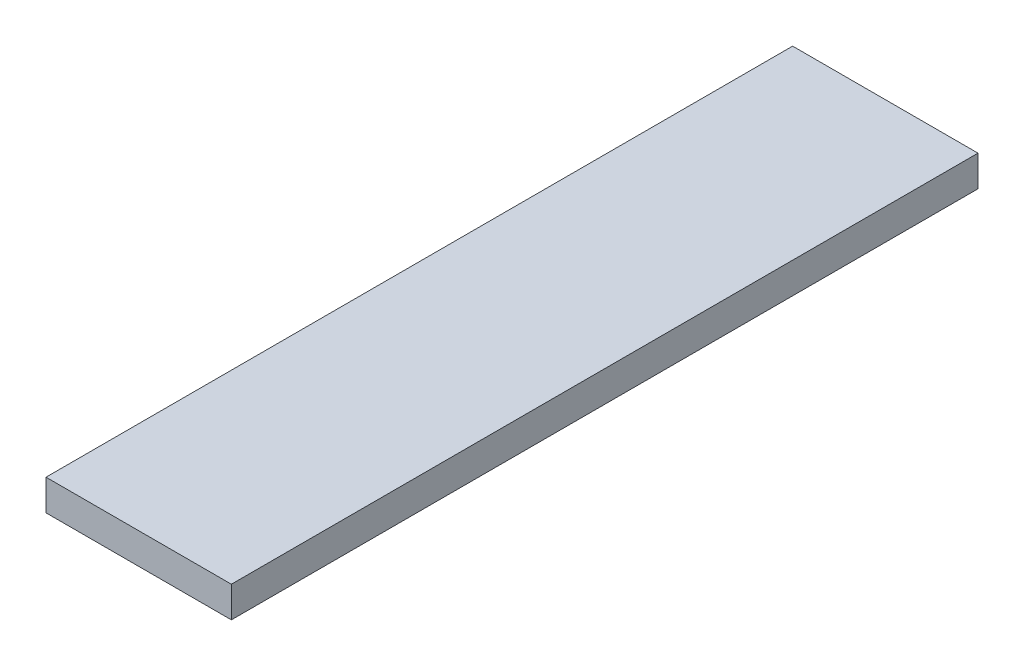
SolidWorks part; units mm, degrees
ref_plane "Front Plane" through (0, 0, 0) normal (0, 0, 1) x (1, 0, 0)
ref_plane "Top Plane" through (0, 0, 0) normal (0, 1, 0) x (1, 0, 0)
ref_plane "Right Plane" through (0, 0, 0) normal (1, 0, 0) x (0, 0, -1)
sketch "Sketch1" plane through (0, 0, 0) normal (0, 0, 1) x (1, 0, 0)
  line L8 (-72.1457, -4.4) -> (-72.1457, -1.6)
  line L9 (-72.1457, -1.6) -> (-86.9457, -1.6)
  line L10 (-86.9457, -1.6) -> (-86.9457, -4.4)
  line L11 (-86.9457, -4.4) -> (-72.1457, -4.4)
  line L12 (-72.1457, -4.4) -> (-72.1457, -1.6)
  line L13 (-72.1457, -1.6) -> (-86.9457, -1.6)
  line L14 (-86.9457, -1.6) -> (-86.9457, -4.4)
  line L15 (-86.9457, -4.4) -> (-72.1457, -4.4)
  dimension "D1" = 0.1
extrude "Boss-Extrude1" add sketch "Sketch1" along normal blind 54
sketch "Sketch2" plane through (0, 0, 0) normal (0, 0, -1) x (-1, 0, 0)
  line L4 (72.3457, -4.2) -> (86.7457, -4.2)
  line L5 (86.7457, -4.2) -> (86.7457, -1.8)
  line L6 (86.7457, -1.8) -> (72.3457, -1.8)
  line L7 (72.3457, -1.8) -> (72.3457, -4.2)
  line L8 (72.1457, -4.4) -> (86.9457, -4.4)
  line L9 (86.9457, -4.4) -> (86.9457, -1.6)
  line L10 (86.9457, -1.6) -> (72.1457, -1.6)
  line L11 (72.1457, -1.6) -> (72.1457, -4.4)
  line L12 (72.1457, -4.4) -> (86.9457, -4.4)
  line L13 (86.9457, -4.4) -> (86.9457, -1.6)
  line L14 (86.9457, -1.6) -> (72.1457, -1.6)
  line L15 (72.1457, -1.6) -> (72.1457, -4.4)
  dimension "D1" = 0
  dimension "D2" = 0.2
extrude "Cut-Extrude1" cut sketch "Sketch2" against normal through all both and the other way through all
sketch "Sketch3" plane through (0, 0, 0) normal (0, 0, -1) x (-1, 0, 0)
  line L1 (72.3457, -1.8) -> (86.7457, -1.8)
  line L2 (72.3457, -1.8) -> (72.3457, -4.2)
  line L3 (72.3457, -4.2) -> (86.7457, -4.2)
  line L4 (86.7457, -1.8) -> (86.7457, -4.2)
extrude "Boss-Extrude2" add sketch "Sketch3" along normal blind 4
